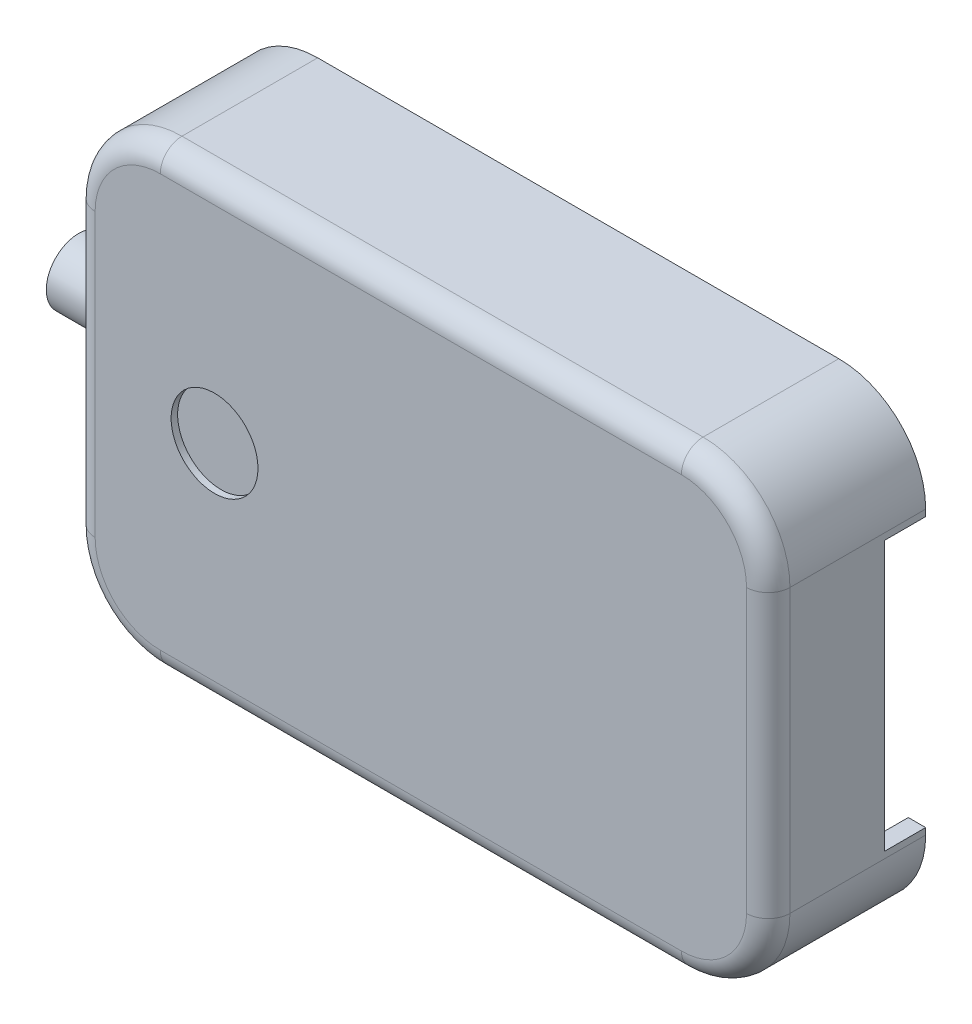
SolidWorks part; units mm, degrees
ref_plane "Front Plane" through (0, 0, 0) normal (0, 0, 1) x (1, 0, 0)
ref_plane "Top Plane" through (0, 0, 0) normal (0, 1, 0) x (1, 0, 0)
ref_plane "Right Plane" through (0, 0, 0) normal (1, 0, 0) x (0, 0, -1)
sketch "Sketch1" plane through (0, 0, 0) normal (0, 0, 1) x (1, 0, 0)
  line L1 (-32, 21) -> (32, 21)
  line L2 (-32, 21) -> (-32, -21)
  line L3 (-32, -21) -> (32, -21)
  line L4 (32, 21) -> (32, -21)
  point P4 (0, 21)
  point P6 (-32, 0)
  dimension "D1" = 64
  dimension "D2" = 42
extrude "Boss-Extrude1" add sketch "Sketch1" along normal blind 14.5
fillet "Fillet1" radius 8 4 edges at (-32, -21, 7.25) (32, -21, 7.25) (-32, 21, 7.25) (32, 21, 7.25)
fillet "Fillet2" radius 2 8 edges at (-29.6569, 18.6569, 14.5) (0, 21, 14.5) (29.6569, 18.6569, 14.5) (32, 0, 14.5) (29.6569, -18.6569, 14.5) (0, -21, 14.5) (-29.6569, -18.6569, 14.5) (-32, 0, 14.5)
shell "Shell1" thickness 1.6
sketch "Sketch2" plane through (32, 0, 0) normal (1, 0, 0) x (0, 0, -1)
  line L1 (0, 12.4) -> (-3.8, 12.4)
  line L2 (0, 12.4) -> (0, -12.4)
  line L3 (0, -12.4) -> (-3.8, -12.4)
  line L4 (-3.8, 12.4) -> (-3.8, -12.4)
  line L5 (0, -13) -> (0, 13) construction
  point P4 (0, 0)
  dimension "D1" = 24.8
  dimension "D2" = 3.8
extrude "Cut-Extrude1" cut sketch "Sketch2" against normal up to next
sketch "Sketch3" plane through (-32, 0, 0) normal (-1, 0, 0) x (0, 0, 1)
  line L0 (0, 13) -> (0, -13) construction
  circle A0 centre (7, 0) radius 3
  dimension "D1" = 6
  dimension "D2" = 7
extrude "Boss-Extrude2" add sketch "Sketch3" along normal blind 7
sketch "Sketch4" plane through (-39, 0, 0) normal (-1, 0, 0) x (0, 0, 1)
  circle A0 centre (7, 0) radius 1.6
  dimension "D1" = 3.2
extrude "Cut-Extrude2" cut sketch "Sketch4" against normal up to next
sketch "Sketch5" plane through (0, 0, 14.5) normal (0, 0, 1) x (1, 0, 0)
  circle A0 centre (-19, 0) radius 4
  dimension "D1" = 8
  dimension "D2" = 19
extrude "Cut-Extrude3" cut sketch "Sketch5" against normal blind 0.6
